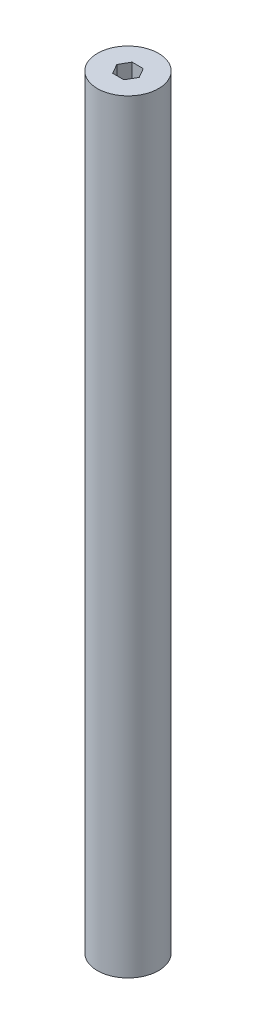
SolidWorks part; units mm, degrees
ref_plane "Front Plane" through (0, 0, 0) normal (0, 0, 1) x (1, 0, 0)
ref_plane "Top Plane" through (0, 0, 0) normal (0, 1, 0) x (1, 0, 0)
ref_plane "Right Plane" through (0, 0, 0) normal (1, 0, 0) x (0, 0, -1)
sketch "Sketch1" plane through (0, 0, 0) normal (0, 1, 0) x (1, 0, 0)
  circle A0 centre (0, 0) radius 60
  dimension "D1" = 120
extrude "Boss-Extrude1" add sketch "Sketch1" along normal blind 1500
sketch "Sketch2" plane through (0, 1500, 0) normal (0, 1, 0) x (1, 0, 0)
  line L1 (-10.9985, 19.05) -> (-21.997, 0)
  line L2 (-21.997, 0) -> (-10.9985, -19.05)
  line L3 (-10.9985, -19.05) -> (10.9985, -19.05)
  line L4 (10.9985, -19.05) -> (21.997, 0)
  line L5 (21.997, 0) -> (10.9985, 19.05)
  line L6 (10.9985, 19.05) -> (-10.9985, 19.05)
  circle A0 centre (0, 0) radius 19.05 construction
  dimension "D1" = 38.1
extrude "Cut-Extrude1" cut sketch "Sketch2" against normal up to next
